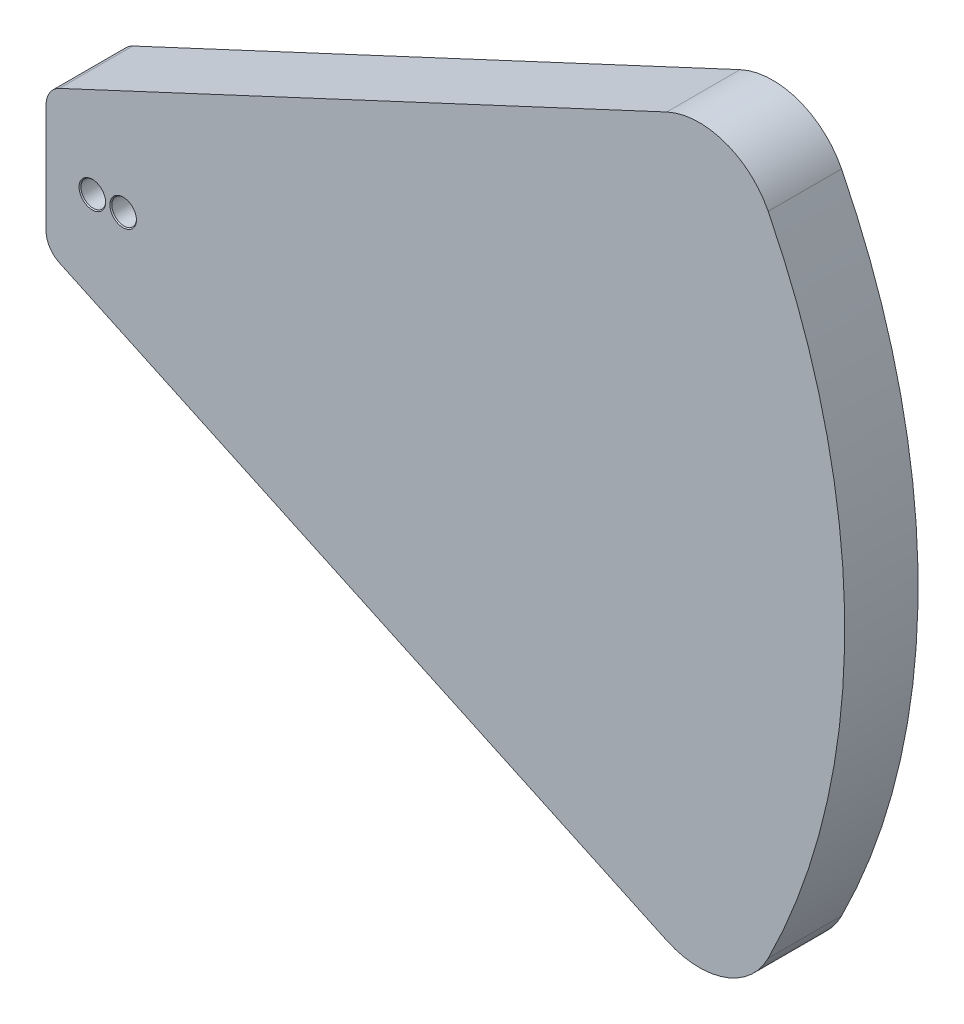
SolidWorks part; units mm, degrees
ref_plane "Front Plane" through (0, 0, 0) normal (1, 0, 0) x (0, 1, 0)
ref_plane "Top Plane" through (0, 0, 0) normal (0, 0, 1) x (0, 1, 0)
ref_plane "Right Plane" through (0, 0, 0) normal (0, 1, 0) x (-1, 0, 0)
sketch "Sketch1" plane through (0, 0, 0) normal (0, 0, 1) x (0, 1, 0)
  line L1 (-4, 0) -> (-4, 10)
  line L2 (-4, 10) -> (4, 10)
  line L3 (4, 10) -> (4, 0)
  line L4 (0, 0) -> (0, 4) construction
  arc A0 (-4, 0) -> (4, 0) centre (0, 0) ccw
  circle A1 centre (0, 0) radius 1.5 construction
  circle A2 centre (0, 4) radius 1.5 construction
  dimension "D1" = 4
  dimension "D4" = 3
  dimension "D2" = 10
  dimension "D3" = 4
sketch "Sketch2" plane through (0, 0, 0) normal (0, 0, 1) x (0, 1, 0)
  line L0 (-9, 10) -> (9, 10)
  line L1 (9, 10) -> (50.4548, -78.9)
  line L2 (-9, 10) -> (-50.4548, -78.9)
  line L3 (-4, 0) -> (-4, 10) construction
  line L4 (-50.4548, -78.9) -> (50.4548, -78.9) construction
  arc A0 (-50.4548, -78.9) -> (50.4548, -78.9) centre (0, 0) ccw
  dimension "D1" = 5
  dimension "D2" = 5
  dimension "D3" = 88.9
  dimension "D4" = 50
extrude "Boss-Extrude1" add sketch "Sketch2" along normal blind 9.525
sketch "Sketch3" plane through (0, 0, 0) normal (0, 0, -1) x (1, 0, 0)
  line L2 (-10, -4.5) -> (-10, 4.5)
  line L4 (-10, -4.5) -> (0, -4.5)
  line L5 (0, 4.5) -> (-10, 4.5)
  line L6 (-10, -4.5) -> (0, -4.5)
  line L7 (0, 4.5) -> (-10, 4.5)
  arc A2 (0, -4.5) -> (0, 4.5) centre (0, 0) ccw
  arc A3 (0, -4.5) -> (0, 4.5) centre (0, 0) ccw
  dimension "D1" = 0.5
extrude "Cut-Extrude2" cut sketch "Sketch3" against normal blind 4
hole_wizard "M3 Clearance Hole1" positions "Sketch4" profile "Sketch5" hole size "M3" standard "ANSI Metric" end condition through all
sketch "Sketch4" plane through (0, 0, 9.525) normal (0, 0, 1) x (0, -1, 0)
  point P0 (0, 0)
  point P3 (0, -4)
sketch "Sketch5" plane through (0, 0, 9.525) normal (1, 0, 0) x (0, -1, 0)
  line L0 (0, 0) -> (0, 9.525)
  line L1 (0, 9.525) -> (1.6, 9.525)
  line L2 (1.6, 9.525) -> (1.6, 0.125)
  line L3 (1.6, 0.125) -> (1.725, 0)
  line L5 (1.725, 0) -> (0, 0)
  line L6 (-1.6, 0.125) -> (-1.725, 0) construction
  line L11 (0, -6.35) -> (0, 107.95) construction
  dimension "Thru Hole Dia." = 3.2
  dimension "Thru Hole Depth" = 9.525
  dimension "Near C'Sink Dia." = 3.45
  dimension "Near C'Sink Angle" = 90
fillet "Fillet1" radius 1 2 edges at (-10, -4.5, 2) (-10, 4.5, 2)
fillet "Fillet2" radius 3 2 edges at (-10, 9, 4.7625) (-10, -9, 4.7625)
fillet "Fillet3" radius 10 2 edges at (78.9, 50.4548, 4.7625) (78.9, -50.4548, 4.7625)
